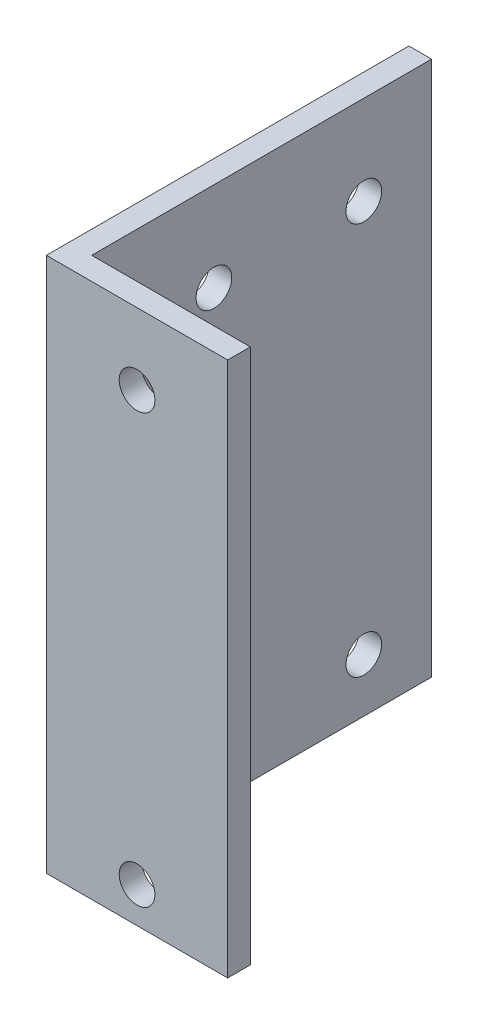
SolidWorks part; units mm, degrees
ref_plane "Alzado" through (0, 0, 0) normal (0, 0, 1) x (1, 0, 0)
ref_plane "Planta" through (0, 0, 0) normal (0, 1, 0) x (1, 0, 0)
ref_plane "Vista lateral" through (0, 0, 0) normal (1, 0, 0) x (0, 0, -1)
sketch "Croquis1" plane through (0, 0, 0) normal (0, 1, 0) x (1, 0, 0)
  line L0 (25.4, 0) -> (0, 0)
  line L1 (0, 0) -> (0, 50.8)
  line L2 (0, 50.8) -> (3.175, 50.8)
  line L3 (3.175, 50.8) -> (3.175, 3.175)
  line L4 (3.175, 3.175) -> (25.4, 3.175)
  line L5 (25.4, 3.175) -> (25.4, 0)
  dimension "D1" = 50.8
  dimension "D2" = 25.4
  dimension "D3" = 3.175
extrude "Saliente-Extruir1" add sketch "Croquis1" along normal blind 80
sketch "Croquis2" plane through (0, 0, 0) normal (-1, 0, 0) x (0, 0, 1)
  line L0 (-50.8, 40) -> (-10.8, 40) construction
  line L1 (-50.8, 80) -> (-50.8, 0) construction
  line L2 (-3.175, 80) -> (-3.175, 0) construction
  line L3 (-50.8, 80) -> (0, 80) construction
  line L4 (-50.8, 0) -> (0, 0) construction
  line L5 (0, 80) -> (0, 0) construction
  line L6 (-30.8, 40) -> (-30.8, 72) construction
  line L7 (-44.8, 72) -> (-16.8, 72) construction
  line L8 (-44.8, 72) -> (-44.8, 8) construction
  line L9 (-44.8, 8) -> (-16.8, 8) construction
  line L10 (-16.8, 72) -> (-16.8, 8) construction
  line L11 (-44.8, 72) -> (-16.8, 8) construction
  line L12 (-44.8, 8) -> (-16.8, 72) construction
  circle A0 centre (-41.3, 67.5) radius 2.5
  circle A1 centre (-20.3, 67.5) radius 2.5
  circle A2 centre (-20.3, 12.5) radius 2.5
  circle A3 centre (-41.3, 12.5) radius 2.5
  point P12 (-30.8, 40)
  dimension "D6" = 5
  dimension "D1" = 40
  dimension "D2" = 3.175
  dimension "D3" = 64
  dimension "D4" = 27.5
  dimension "D5" = 10.5
  dimension "D7" = 28
extrude "Cortar-Extruir1" cut sketch "Croquis2" against normal through all
sketch "Croquis3" plane through (0, 0, 0) normal (0, 0, 1) x (1, 0, 0)
  line L0 (12.7, 80) -> (12.7, 0) construction
  line L1 (0, 80) -> (25.4, 80) construction
  line L2 (0, 0) -> (25.4, 0) construction
  line L3 (12.7, 40) -> (0, 40) construction
  line L4 (0, 80) -> (0, 0) construction
  circle A0 centre (12.7, 70) radius 2.5
  circle A2 centre (12.7, 10) radius 2.5
  dimension "D1" = 5
  dimension "D2" = 30
extrude "Cortar-Extruir2" cut sketch "Croquis3" against normal through all
sketch "Croquis4" plane through (0, 0, 0) normal (0, 0, 1) x (1, 0, 0)
  line L0 (0, 0) -> (25.4, 0) construction
  line L1 (-2.3, 5) -> (27.7, 5)
  line L2 (-2.3, 5) -> (-2.3, -5)
  line L3 (-2.3, -5) -> (27.7, -5)
  line L4 (27.7, 5) -> (27.7, -5)
  line L5 (-2.3, 5) -> (27.7, -5) construction
  line L6 (-2.3, -5) -> (27.7, 5) construction
  point P0 (12.7, 0)
  dimension "D1" = 10
  dimension "D2" = 30
extrude "Cortar-Extruir3" cut sketch "Croquis4" against normal through all
